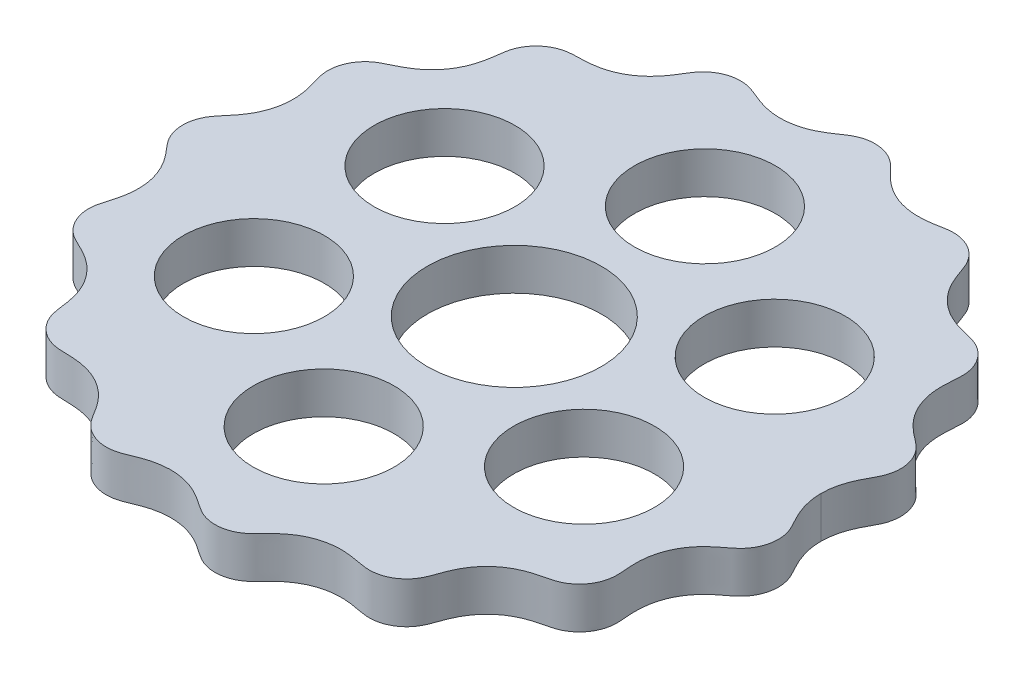
SolidWorks part; units mm, degrees
ref_plane "Front Plane" through (0, 0, 0) normal (0, 0, 1) x (1, 0, 0)
ref_plane "Top Plane" through (0, 0, 0) normal (0, 1, 0) x (1, 0, 0)
ref_plane "Right Plane" through (0, 0, 0) normal (1, 0, 0) x (0, 0, -1)
sketch "Sketch1" plane through (0, 0, 0) normal (0, 1, 0) x (1, 0, 0)
  circle A0 centre (0, 0) radius 10.5
  circle A1 centre (0, 0) radius 23 construction
  circle A2 centre (0, 23) radius 8.5
  circle A3 centre (19.9186, 11.5) radius 8.5
  circle A4 centre (19.9186, -11.5) radius 8.5
  circle A5 centre (0, -23) radius 8.5
  circle A6 centre (-19.9186, -11.5) radius 8.5
  circle A7 centre (-19.9186, 11.5) radius 8.5
  spline S0 degree 4 poles (38.6756, 9.5405) (38.7869, 9.3354) (38.9807, 8.9098) (39.18, 8.2438) (39.2638, 7.3275) (39.17, 6.4698) (38.9321, 5.7015) (38.5995, 5.0253) (38.2553, 4.4109) (37.9563, 3.8443) (37.7129, 3.322) (37.522, 2.8468) (37.3939, 2.4766) (37.2981, 2.1548) (37.2278, 1.884) (37.1776, 1.6659) (37.1334, 1.4465) (37.0953, 1.226) (37.0635, 1.0045) (37.0411, 0.8091) (37.0259, 0.6435) (37.0159, 0.5055) (37.0095, 0.392) (37.0035, 0.2438) (36.9999, 0.079) (36.9994, -0.0361) (37.0025, -0.21) (37.0079, -0.366) (37.0181, -0.5474) (37.0358, -0.7626) (37.0623, -1.0007) (37.0996, -1.2541) (37.1417, -1.4901) (37.1867, -1.7077) (37.276, -2.0862) (37.4326, -2.6197) (37.6503, -3.1917) (37.9334, -3.7956) (38.206, -4.3157) (38.4505, -4.7606) (38.7069, -5.2352) (38.9418, -5.7567) (39.1379, -6.3788) (39.248, -7.1039) (39.2286, -7.94) (39.0193, -8.8558) (38.5776, -9.8235) (37.821, -10.7544) (36.8481, -11.435) (35.9255, -12.1707) (35.1552, -12.9314) (34.5438, -13.6951) (33.8952, -14.742) (33.4284, -15.8904) (33.1613, -17.1041) (33.0908, -18.2767) (33.1179, -19.1348) (33.1846, -19.9227) (33.2426, -20.6446) (33.2196, -21.4379) (33.0363, -22.2817) (32.6622, -23.1285) (32.0787, -23.9264) (31.2705, -24.6475) (30.2129, -25.1958) (29.0562, -25.4259) (27.9212, -25.7148) (26.9129, -26.088) (26.0467, -26.5265) (25.2315, -27.0702) (24.4863, -27.7162) (23.8232, -28.4568) (23.2548, -29.2804) (22.819, -30.1054) (22.4892, -30.9045) (22.2262, -31.656) (21.9863, -32.3444) (21.6457, -33.0672) (21.1369, -33.7721) (20.4446, -34.4052) (19.5735, -34.9081) (18.6791, -35.1912) (17.8142, -35.2793) (17.018, -35.2129) (16.3018, -35.0765) (15.5195, -34.9284) (14.6625, -34.8147) (13.4804, -34.7697) (12.2411, -34.9196) (11.052, -35.2755) (9.9494, -35.8202) (9.1364, -36.3513) (8.3091, -37.0378) (7.4914, -37.8764) (6.7137, -38.763) (5.7101, -39.4048) (4.6815, -39.7442) (3.6987, -39.8506) (2.7784, -39.7512) (1.9559, -39.488) (1.2575, -39.1113) (0.6613, -38.7001) (0.0122, -38.2484) (-0.7173, -37.7958) (-1.768, -37.2706) (-2.9527, -36.8951) (-4.1807, -36.7251) (-5.4116, -36.7634) (-6.3787, -36.9109) (-7.4226, -37.1978) (-8.5211, -37.6287) (-9.5969, -38.1313) (-10.7814, -38.3206) (-11.8653, -38.2177) (-12.81, -37.9179) (-13.7654, -37.3701) (-14.6397, -36.51) (-15.225, -35.4471) (-15.8752, -34.4321) (-16.7227, -33.382) (-17.6452, -32.5494) (-18.6953, -31.8812) (-19.8393, -31.4031) (-20.7931, -31.1347) (-21.8817, -30.9645) (-23.0854, -30.9087) (-24.2988, -30.9334) (-25.4807, -30.6062) (-26.4329, -30.0527) (-27.1648, -29.3844) (-27.7959, -28.4973) (-28.2242, -27.3768) (-28.3269, -26.1938) (-28.503, -25.027) (-28.7764, -23.9796) (-29.1322, -23.0683) (-29.7145, -21.9831) (-30.4757, -21.0047) (-31.3933, -20.1664) (-32.3735, -19.5191) (-33.1302, -19.1136) (-33.8459, -18.7774) (-34.5001, -18.4667) (-35.1756, -18.0501) (-35.8147, -17.4694) (-36.361, -16.7221) (-36.7603, -15.8178) (-36.9806, -14.7573) (-36.9266, -13.5673) (-36.5476, -12.4504) (-36.2302, -11.323) (-36.0493, -10.2632) (-35.996, -9.2938) (-36.0592, -8.316) (-36.2461, -7.3476) (-36.5559, -6.4031) (-36.985, -5.499) (-37.4816, -4.7092) (-38.0086, -4.024) (-38.5281, -3.4205) (-39.0041, -2.8683) (-39.353, -2.3666) (-39.5782, -1.9309) (-39.7176, -1.5888) (-39.7983, -1.3525) (-39.8659, -1.1123) (-39.9132, -0.899) (-39.9453, -0.714) (-39.9664, -0.5608) (-39.98, -0.4381) (-39.9901, -0.3108) (-39.9969, -0.1759) (-40.0009, -0.0264) (-39.9998, 0.101) (-39.9919, 0.3019) (-39.9779, 0.461) (-39.962, 0.5936) (-39.9468, 0.7) (-39.9245, 0.8336) (-39.8928, 0.9931) (-39.8356, 1.2296) (-39.7321, 1.5628) (-39.5698, 1.9581) (-39.3263, 2.4015) (-39.0212, 2.8342) (-38.6301, 3.3062) (-38.1713, 3.8306) (-37.748, 4.3543) (-37.3751, 4.8861) (-37.0367, 5.4401) (-36.6355, 6.2077) (-36.2169, 7.3272) (-36.0304, 8.4018) (-36.0089, 9.2689) (-36.0283, 9.7011) knots 0 0 0 0 0 0.006139 0.012278 0.018165 0.024053 0.028687 0.033322 0.037957 0.042591 0.045535 0.048479 0.051424 0.052896 0.054368 0.05584 0.057312 0.058784 0.060256 0.061728 0.062464 0.0632 0.063936 0.064672 0.066144 0.067103 0.068061 0.06902 0.069978 0.071895 0.073812 0.075274 0.076735 0.078197 0.079659 0.085505 0.091352 0.094275 0.097198 0.100954 0.104711 0.108467 0.112223 0.11807 0.123916 0.130339 0.136761 0.145879 0.154997 0.161421 0.167846 0.17427 0.180694 0.193737 0.200258 0.206779 0.211542 0.216304 0.221067 0.225829 0.232349 0.238869 0.245245 0.251622 0.260677 0.269731 0.27611 0.282488 0.288866 0.295244 0.301811 0.308378 0.314945 0.321512 0.326307 0.331102 0.335897 0.340691 0.347256 0.353821 0.360386 0.366951 0.371745 0.37654 0.381335 0.38613 0.392697 0.399264 0.412398 0.418776 0.425154 0.431532 0.437911 0.446965 0.45602 0.462396 0.468773 0.475293 0.481813 0.486575 0.491338 0.4961 0.500863 0.507384 0.513905 0.526948 0.533372 0.539796 0.54622 0.552645 0.561763 0.570881 0.577303 0.583726 0.59023 0.596734 0.606103 0.615471 0.621978 0.628484 0.641498 0.648004 0.654511 0.661018 0.667524 0.676893 0.686261 0.692765 0.699269 0.705692 0.712114 0.721232 0.730351 0.736775 0.743199 0.749623 0.756047 0.76909 0.775611 0.782133 0.786895 0.791658 0.79642 0.801182 0.807702 0.814222 0.820599 0.826976 0.83603 0.845085 0.851463 0.857841 0.864219 0.870597 0.877164 0.883732 0.890299 0.896866 0.90166 0.906455 0.91125 0.916045 0.917686 0.919327 0.920968 0.922609 0.924251 0.925071 0.925892 0.926712 0.927533 0.928354 0.929174 0.930597 0.93202 0.932732 0.933444 0.934155 0.934867 0.93629 0.937713 0.940559 0.944036 0.947513 0.950991 0.954468 0.960159 0.965851 0.968697 0.971542 0.977234 0.988617 1 1 1 1 1 construction
  spline S1 degree 4 poles (37, 0) (37, -0.0314) (37.0005, -0.095) (37.0025, -0.21) (37.0079, -0.366) (37.0181, -0.5474) (37.0358, -0.7626) (37.0623, -1.0007) (37.0996, -1.2541) (37.1417, -1.4901) (37.1867, -1.7077) (37.276, -2.0862) (37.4326, -2.6197) (37.6503, -3.1917) (37.9334, -3.7956) (38.206, -4.3157) (38.4505, -4.7606) (38.7069, -5.2352) (38.9418, -5.7567) (39.1379, -6.3788) (39.248, -7.1039) (39.2286, -7.94) (39.0193, -8.8558) (38.5776, -9.8235) (37.821, -10.7544) (36.8481, -11.435) (35.9255, -12.1707) (35.1552, -12.9314) (34.5438, -13.6951) (33.8952, -14.742) (33.4284, -15.8904) (33.1613, -17.1041) (33.0908, -18.2767) (33.1179, -19.1348) (33.1846, -19.9227) (33.2426, -20.6446) (33.2196, -21.4379) (33.0363, -22.2817) (32.6622, -23.1285) (32.0787, -23.9264) (31.2705, -24.6475) (30.2129, -25.1958) (29.0562, -25.4259) (27.9212, -25.7148) (26.9129, -26.088) (26.0467, -26.5265) (25.2315, -27.0702) (24.4863, -27.7162) (23.8232, -28.4568) (23.2548, -29.2804) (22.819, -30.1054) (22.4892, -30.9045) (22.2262, -31.656) (21.9863, -32.3444) (21.6457, -33.0672) (21.1369, -33.7721) (20.4446, -34.4052) (19.5735, -34.9081) (18.6791, -35.1912) (17.8142, -35.2793) (17.018, -35.2129) (16.3018, -35.0765) (15.5195, -34.9284) (14.6625, -34.8147) (13.4804, -34.7697) (12.2411, -34.9196) (11.052, -35.2755) (9.9494, -35.8202) (9.1364, -36.3513) (8.3091, -37.0378) (7.4914, -37.8764) (6.7137, -38.763) (5.7101, -39.4048) (4.6815, -39.7442) (3.6987, -39.8506) (2.7784, -39.7512) (1.9559, -39.488) (1.2575, -39.1113) (0.6613, -38.7001) (0.0122, -38.2484) (-0.7173, -37.7958) (-1.768, -37.2706) (-2.9527, -36.8951) (-4.1807, -36.7251) (-5.4116, -36.7634) (-6.3787, -36.9109) (-7.4226, -37.1978) (-8.5211, -37.6287) (-9.5969, -38.1313) (-10.7814, -38.3206) (-11.8653, -38.2177) (-12.81, -37.9179) (-13.7654, -37.3701) (-14.6397, -36.51) (-15.225, -35.4471) (-15.8752, -34.4321) (-16.7227, -33.382) (-17.6452, -32.5494) (-18.6953, -31.8812) (-19.8393, -31.4031) (-20.7931, -31.1347) (-21.8817, -30.9645) (-23.0854, -30.9087) (-24.2988, -30.9334) (-25.4807, -30.6062) (-26.4329, -30.0527) (-27.1648, -29.3844) (-27.7959, -28.4973) (-28.2242, -27.3768) (-28.3269, -26.1938) (-28.503, -25.027) (-28.7764, -23.9796) (-29.1322, -23.0683) (-29.7145, -21.9831) (-30.4757, -21.0047) (-31.3933, -20.1664) (-32.3735, -19.5191) (-33.1302, -19.1136) (-33.8459, -18.7774) (-34.5001, -18.4667) (-35.1756, -18.0501) (-35.8147, -17.4694) (-36.361, -16.7221) (-36.7603, -15.8178) (-36.9806, -14.7573) (-36.9266, -13.5673) (-36.5476, -12.4504) (-36.2302, -11.323) (-36.0493, -10.2632) (-35.996, -9.2938) (-36.0592, -8.316) (-36.2461, -7.3476) (-36.5559, -6.4031) (-36.985, -5.499) (-37.4816, -4.7092) (-38.0086, -4.024) (-38.5281, -3.4205) (-39.0041, -2.8683) (-39.353, -2.3666) (-39.5782, -1.9309) (-39.7176, -1.5888) (-39.7983, -1.3525) (-39.8659, -1.1123) (-39.9132, -0.899) (-39.9453, -0.714) (-39.9664, -0.5608) (-39.98, -0.4381) (-39.9901, -0.3108) (-39.9969, -0.1759) (-39.9994, -0.0812) (-40, -0.0269) (-40, 0) knots 0.066144 0.066144 0.066144 0.066144 0.066144 0.067103 0.068061 0.06902 0.069978 0.071895 0.073812 0.075274 0.076735 0.078197 0.079659 0.085505 0.091352 0.094275 0.097198 0.100954 0.104711 0.108467 0.112223 0.11807 0.123916 0.130339 0.136761 0.145879 0.154997 0.161421 0.167846 0.17427 0.180694 0.193737 0.200258 0.206779 0.211542 0.216304 0.221067 0.225829 0.232349 0.238869 0.245245 0.251622 0.260677 0.269731 0.27611 0.282488 0.288866 0.295244 0.301811 0.308378 0.314945 0.321512 0.326307 0.331102 0.335897 0.340691 0.347256 0.353821 0.360386 0.366951 0.371745 0.37654 0.381335 0.38613 0.392697 0.399264 0.412398 0.418776 0.425154 0.431532 0.437911 0.446965 0.45602 0.462396 0.468773 0.475293 0.481813 0.486575 0.491338 0.4961 0.500863 0.507384 0.513905 0.526948 0.533372 0.539796 0.54622 0.552645 0.561763 0.570881 0.577303 0.583726 0.59023 0.596734 0.606103 0.615471 0.621978 0.628484 0.641498 0.648004 0.654511 0.661018 0.667524 0.676893 0.686261 0.692765 0.699269 0.705692 0.712114 0.721232 0.730351 0.736775 0.743199 0.749623 0.756047 0.76909 0.775611 0.782133 0.786895 0.791658 0.79642 0.801182 0.807702 0.814222 0.820599 0.826976 0.83603 0.845085 0.851463 0.857841 0.864219 0.870597 0.877164 0.883732 0.890299 0.896866 0.90166 0.906455 0.91125 0.916045 0.917686 0.919327 0.920968 0.922609 0.924251 0.925071 0.925892 0.926712 0.927533 0.928354 0.929174 0.929174 0.929174 0.929174 0.929174
  spline S2 degree 4 poles (-36.0283, -9.7011) (-36.0089, -9.2689) (-36.025, -8.6185) (-36.1423, -7.7571) (-36.4452, -6.7165) (-36.7773, -5.9157) (-37.1923, -5.1548) (-37.6189, -4.528) (-38.0202, -4.0177) (-38.3849, -3.5864) (-38.6992, -3.2229) (-38.979, -2.8851) (-39.2119, -2.5638) (-39.3869, -2.2834) (-39.514, -2.0514) (-39.6452, -1.7744) (-39.7518, -1.4995) (-39.8356, -1.2297) (-39.8991, -0.9667) (-39.9398, -0.7534) (-39.9703, -0.5412) (-39.9907, -0.329) (-39.9998, -0.1024) (-40.0009, 0.0274) (-39.9969, 0.174) (-39.9901, 0.3085) (-39.98, 0.4378) (-39.9664, 0.5616) (-39.9495, 0.6838) (-39.9292, 0.8064) (-39.9056, 0.9291) (-39.8785, 1.0511) (-39.8405, 1.2024) (-39.7882, 1.382) (-39.7175, 1.5887) (-39.6127, 1.8466) (-39.4787, 2.1231) (-39.3107, 2.4141) (-39.1049, 2.7153) (-38.8813, 3.0032) (-38.6471, 3.2825) (-38.3498, 3.6277) (-37.9529, 4.0962) (-37.4817, 4.7093) (-36.9849, 5.4989) (-36.556, 6.4033) (-36.1702, 7.5783) (-35.9868, 8.7988) (-36.0091, 10.0244) (-36.2006, 11.152) (-36.4085, 11.955) (-36.6307, 12.6803) (-36.8216, 13.3417) (-36.9923, 14.3318) (-36.9049, 15.4222) (-36.5044, 16.5243) (-35.815, 17.4697) (-35.1754, 18.05) (-34.5001, 18.4666) (-33.846, 18.7777) (-32.9056, 19.2181) (-31.7252, 19.8872) (-30.4396, 20.9666) (-29.2852, 22.5861) (-28.6866, 24.1372) (-28.4341, 25.439) (-28.3116, 26.4395) (-28.2186, 27.1266) (-28.0361, 27.8709) (-27.6947, 28.6385) (-27.1647, 29.385) (-26.4334, 30.0526) (-25.6346, 30.5161) (-24.8231, 30.7888) (-24.0469, 30.8992) (-23.3347, 30.9203) (-22.3064, 30.9378) (-20.9635, 31.0586) (-19.3449, 31.507) (-17.6134, 32.5067) (-16.4158, 33.6842) (-15.6397, 34.7868) (-15.1104, 35.6686) (-14.7361, 36.2748) (-14.2524, 36.8918) (-13.6104, 37.4583) (-12.8096, 37.9183) (-11.8658, 38.2178) (-10.9543, 38.3035) (-10.1188, 38.2154) (-9.383, 38.0014) (-8.7414, 37.7383) (-7.8138, 37.3442) (-6.5601, 36.912) (-4.9175, 36.6548) (-2.9379, 36.8448) (-1.3603, 37.4184) (-0.1906, 38.1061) (0.661, 38.7003) (1.2575, 39.1113) (1.9559, 39.4878) (2.7783, 39.7515) (3.9418, 39.8759) (5.0965, 39.6717) (6.0845, 39.2022) (6.8565, 38.5593) (7.3339, 38.0633) (7.8509, 37.5082) (8.4424, 36.9267) (9.3231, 36.1969) (10.5884, 35.4356) (11.9992, 34.9487) (13.4803, 34.7698) (14.6625, 34.8147) (15.5194, 34.9284) (16.3018, 35.0765) (17.0179, 35.2129) (17.8142, 35.2793) (18.6791, 35.1911) (19.5735, 34.9082) (20.4445, 34.4052) (21.137, 33.7722) (21.5918, 33.1415) (21.8696, 32.5926) (22.0759, 32.0862) (22.2266, 31.6561) (22.3766, 31.2261) (22.5937, 30.6514) (22.8615, 30.0249) (23.2551, 29.2802) (23.8228, 28.4571) (24.6491, 27.5346) (25.8025, 26.6152) (27.2181, 25.9053) (28.8176, 25.4727) (30.4528, 25.1488) (31.6988, 24.3833) (32.5609, 23.3518) (33.0376, 22.2818) (33.2189, 21.4379) (33.243, 20.6446) (33.1848, 19.9227) (33.0963, 18.888) (33.0853, 17.5312) (33.3775, 15.8781) (34.2027, 14.0687) (35.2468, 12.7747) (36.2479, 11.9052) (37.0531, 11.2989) (37.6016, 10.8748) (38.155, 10.3445) (38.649, 9.665) (39.0305, 8.8328) (39.243, 7.8658) (39.2451, 6.9422) (39.0753, 6.1031) (38.7832, 5.3754) (38.4446, 4.7486) (38.1266, 4.173) (37.8549, 3.634) (37.633, 3.1317) (37.4786, 2.7272) (37.3626, 2.3747) (37.2774, 2.0775) (37.2164, 1.8379) (37.1626, 1.5964) (37.1163, 1.3536) (37.0774, 1.1094) (37.0502, 0.8937) (37.0316, 0.7109) (37.0194, 0.5584) (37.0116, 0.4331) (37.0042, 0.2696) (36.9994, 0.0658) (36.9993, -0.087) (37.0071, -0.3742) (37.0226, -0.616) (37.0458, -0.8587) (37.0767, -1.1038) (37.1247, -1.4076) (37.1852, -1.7092) (37.2578, -2.0082) (37.3591, -2.3632) (37.4739, -2.7141) (37.627, -3.1167) (37.8469, -3.6171) (38.1165, -4.154) (38.4326, -4.7273) (38.7709, -5.3508) (39.0661, -6.0733) (39.2414, -6.9072) (39.2472, -7.9128) (39.0566, -8.7198) (38.8323, -9.2517) (38.6756, -9.5405) knots 0 0 0 0 0 0.011383 0.017074 0.022766 0.028458 0.034149 0.039841 0.042687 0.045532 0.049009 0.052487 0.054225 0.055964 0.057702 0.059441 0.062287 0.06371 0.065133 0.066556 0.06798 0.069403 0.070826 0.071646 0.072467 0.073288 0.074108 0.074929 0.075749 0.07657 0.077391 0.078211 0.079032 0.080673 0.082314 0.083955 0.086353 0.08875 0.091148 0.093545 0.095942 0.09834 0.103134 0.109701 0.116269 0.122836 0.129403 0.142159 0.148537 0.154915 0.159443 0.16397 0.168497 0.173024 0.185778 0.192298 0.198818 0.20358 0.208342 0.213105 0.217867 0.23091 0.243953 0.256801 0.269649 0.274209 0.278768 0.283327 0.287886 0.294308 0.300731 0.307235 0.313739 0.318423 0.323107 0.327792 0.332476 0.345489 0.358502 0.371516 0.384529 0.389213 0.393897 0.398582 0.403266 0.40977 0.416274 0.422697 0.429119 0.433678 0.438237 0.442796 0.447355 0.460204 0.473052 0.486095 0.499137 0.5039 0.508662 0.513425 0.518187 0.524707 0.531227 0.54398 0.548508 0.553035 0.557562 0.56209 0.568468 0.574846 0.587602 0.600736 0.607303 0.613871 0.618665 0.62346 0.628255 0.633049 0.639614 0.646179 0.652744 0.659309 0.664104 0.666501 0.668898 0.673693 0.67609 0.678488 0.685055 0.691622 0.698189 0.704756 0.717512 0.730269 0.739323 0.748378 0.761131 0.767651 0.774171 0.778933 0.783696 0.788458 0.793221 0.806263 0.819306 0.832154 0.845003 0.849562 0.854121 0.85868 0.863239 0.869662 0.876084 0.882588 0.889092 0.893777 0.898461 0.903145 0.907829 0.911083 0.914336 0.917589 0.919216 0.920842 0.922469 0.924096 0.925722 0.927349 0.928976 0.929789 0.930602 0.931416 0.932229 0.933856 0.935474 0.937093 0.938711 0.94033 0.941948 0.943567 0.946804 0.948422 0.950041 0.953278 0.956515 0.959752 0.964416 0.96908 0.973744 0.978408 0.984882 0.991355 1 1 1 1 1 construction
  spline S3 degree 4 poles (-40, 0) (-40, 0.0269) (-39.9994, 0.0811) (-39.9969, 0.174) (-39.9901, 0.3085) (-39.98, 0.4378) (-39.9664, 0.5616) (-39.9495, 0.6838) (-39.9292, 0.8064) (-39.9056, 0.9291) (-39.8785, 1.0511) (-39.8405, 1.2024) (-39.7882, 1.382) (-39.7175, 1.5887) (-39.6127, 1.8466) (-39.4787, 2.1231) (-39.3107, 2.4141) (-39.1049, 2.7153) (-38.8813, 3.0032) (-38.6471, 3.2825) (-38.3498, 3.6277) (-37.9529, 4.0962) (-37.4817, 4.7093) (-36.9849, 5.4989) (-36.556, 6.4033) (-36.1702, 7.5783) (-35.9868, 8.7988) (-36.0091, 10.0244) (-36.2006, 11.152) (-36.4085, 11.955) (-36.6307, 12.6803) (-36.8216, 13.3417) (-36.9923, 14.3318) (-36.9049, 15.4222) (-36.5044, 16.5243) (-35.815, 17.4697) (-35.1754, 18.05) (-34.5001, 18.4666) (-33.846, 18.7777) (-32.9056, 19.2181) (-31.7252, 19.8872) (-30.4396, 20.9666) (-29.2852, 22.5861) (-28.6866, 24.1372) (-28.4341, 25.439) (-28.3116, 26.4395) (-28.2186, 27.1266) (-28.0361, 27.8709) (-27.6947, 28.6385) (-27.1647, 29.385) (-26.4334, 30.0526) (-25.6346, 30.5161) (-24.8231, 30.7888) (-24.0469, 30.8992) (-23.3347, 30.9203) (-22.3064, 30.9378) (-20.9635, 31.0586) (-19.3449, 31.507) (-17.6134, 32.5067) (-16.4158, 33.6842) (-15.6397, 34.7868) (-15.1104, 35.6686) (-14.7361, 36.2748) (-14.2524, 36.8918) (-13.6104, 37.4583) (-12.8096, 37.9183) (-11.8658, 38.2178) (-10.9543, 38.3035) (-10.1188, 38.2154) (-9.383, 38.0014) (-8.7414, 37.7383) (-7.8138, 37.3442) (-6.5601, 36.912) (-4.9175, 36.6548) (-2.9379, 36.8448) (-1.3603, 37.4184) (-0.1906, 38.1061) (0.661, 38.7003) (1.2575, 39.1113) (1.9559, 39.4878) (2.7783, 39.7515) (3.9418, 39.8759) (5.0965, 39.6717) (6.0845, 39.2022) (6.8565, 38.5593) (7.3339, 38.0633) (7.8509, 37.5082) (8.4424, 36.9267) (9.3231, 36.1969) (10.5884, 35.4356) (11.9992, 34.9487) (13.4803, 34.7698) (14.6625, 34.8147) (15.5194, 34.9284) (16.3018, 35.0765) (17.0179, 35.2129) (17.8142, 35.2793) (18.6791, 35.1911) (19.5735, 34.9082) (20.4445, 34.4052) (21.137, 33.7722) (21.5918, 33.1415) (21.8696, 32.5926) (22.0759, 32.0862) (22.2266, 31.6561) (22.3766, 31.2261) (22.5937, 30.6514) (22.8615, 30.0249) (23.2551, 29.2802) (23.8228, 28.4571) (24.6491, 27.5346) (25.8025, 26.6152) (27.2181, 25.9053) (28.8176, 25.4727) (30.4528, 25.1488) (31.6988, 24.3833) (32.5609, 23.3518) (33.0376, 22.2818) (33.2189, 21.4379) (33.243, 20.6446) (33.1848, 19.9227) (33.0963, 18.888) (33.0853, 17.5312) (33.3775, 15.8781) (34.2027, 14.0687) (35.2468, 12.7747) (36.2479, 11.9052) (37.0531, 11.2989) (37.6016, 10.8748) (38.155, 10.3445) (38.649, 9.665) (39.0305, 8.8328) (39.243, 7.8658) (39.2451, 6.9422) (39.0753, 6.1031) (38.7832, 5.3754) (38.4446, 4.7486) (38.1266, 4.173) (37.8549, 3.634) (37.633, 3.1317) (37.4786, 2.7272) (37.3626, 2.3747) (37.2774, 2.0775) (37.2164, 1.8379) (37.1626, 1.5964) (37.1163, 1.3536) (37.0774, 1.1094) (37.0502, 0.8937) (37.0316, 0.7109) (37.0194, 0.5584) (37.0116, 0.4331) (37.0042, 0.2696) (37.001, 0.1335) (37, 0.0534) (37, 0) knots 0.070826 0.070826 0.070826 0.070826 0.070826 0.071646 0.072467 0.073288 0.074108 0.074929 0.075749 0.07657 0.077391 0.078211 0.079032 0.080673 0.082314 0.083955 0.086353 0.08875 0.091148 0.093545 0.095942 0.09834 0.103134 0.109701 0.116269 0.122836 0.129403 0.142159 0.148537 0.154915 0.159443 0.16397 0.168497 0.173024 0.185778 0.192298 0.198818 0.20358 0.208342 0.213105 0.217867 0.23091 0.243953 0.256801 0.269649 0.274209 0.278768 0.283327 0.287886 0.294308 0.300731 0.307235 0.313739 0.318423 0.323107 0.327792 0.332476 0.345489 0.358502 0.371516 0.384529 0.389213 0.393897 0.398582 0.403266 0.40977 0.416274 0.422697 0.429119 0.433678 0.438237 0.442796 0.447355 0.460204 0.473052 0.486095 0.499137 0.5039 0.508662 0.513425 0.518187 0.524707 0.531227 0.54398 0.548508 0.553035 0.557562 0.56209 0.568468 0.574846 0.587602 0.600736 0.607303 0.613871 0.618665 0.62346 0.628255 0.633049 0.639614 0.646179 0.652744 0.659309 0.664104 0.666501 0.668898 0.673693 0.67609 0.678488 0.685055 0.691622 0.698189 0.704756 0.717512 0.730269 0.739323 0.748378 0.761131 0.767651 0.774171 0.778933 0.783696 0.788458 0.793221 0.806263 0.819306 0.832154 0.845003 0.849562 0.854121 0.85868 0.863239 0.869662 0.876084 0.882588 0.889092 0.893777 0.898461 0.903145 0.907829 0.911083 0.914336 0.917589 0.919216 0.920842 0.922469 0.924096 0.925722 0.927349 0.928976 0.929789 0.930602 0.931416 0.932229 0.933856 0.933856 0.933856 0.933856 0.933856
  point P24 (0, 0)
  dimension "D1" = 21
  dimension "D2" = 17
  dimension "D4" = 46
  dimension "D3" = 6
extrude "Boss-Extrude1" add sketch "Sketch1" along normal blind 5
